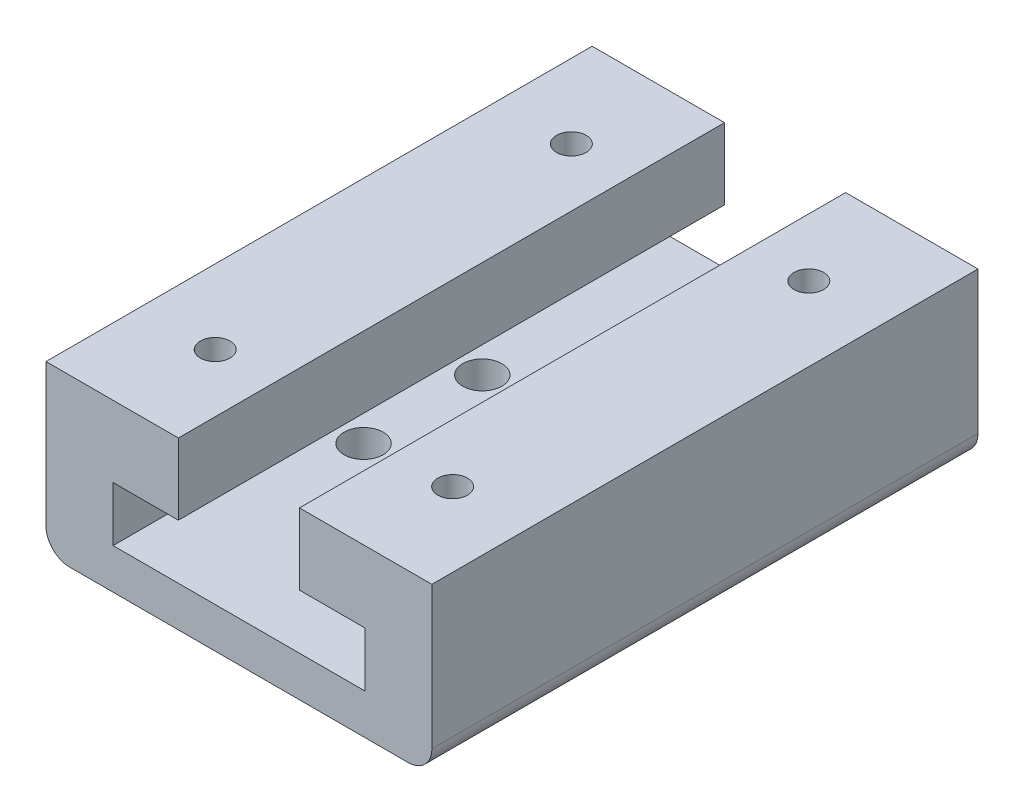
SolidWorks part; units mm, degrees
ref_plane "前视基准面" through (0, 0, 0) normal (0, 0, 1) x (1, 0, 0)
ref_plane "上视基准面" through (0, 0, 0) normal (0, 1, 0) x (1, 0, 0)
ref_plane "右视基准面" through (0, 0, 0) normal (1, 0, 0) x (0, 0, -1)
sketch "草图1" plane through (0, 0, 0) normal (0, 1, 0) x (1, 0, 0)
  line L1 (16.25, -23) -> (-16.25, -23)
  line L2 (16.25, -23) -> (16.25, 23)
  line L3 (16.25, 23) -> (-16.25, 23)
  line L4 (-16.25, -23) -> (-16.25, 23)
  line L5 (16.25, -23) -> (-16.25, 23) construction
  line L6 (16.25, 23) -> (-16.25, -23) construction
  point P0 (0, 0)
  dimension "D1" = 32.5
  dimension "D2" = 46
extrude "凸台-拉伸1" add sketch "草图1" along normal blind 14
sketch "草图2" plane through (0, 0, -23) normal (0, 0, -1) x (-1, 0, 0)
  line L0 (-16.25, 14) -> (16.25, 14) construction
  line L1 (-5.1, 8) -> (5.1, 8)
  line L2 (-5.1, 8) -> (-5.1, 14)
  line L3 (-5.1, 14) -> (5.1, 14)
  line L4 (5.1, 8) -> (5.1, 14)
  line L5 (-5.1, 8) -> (5.1, 14) construction
  line L6 (-5.1, 14) -> (5.1, 8) construction
  line L8 (-10.6, 3.4) -> (10.6, 3.4)
  line L9 (-10.6, 3.4) -> (-10.6, 8)
  line L10 (-10.6, 8) -> (10.6, 8)
  line L11 (10.6, 3.4) -> (10.6, 8)
  line L12 (-10.6, 3.4) -> (10.6, 8) construction
  line L13 (-10.6, 8) -> (10.6, 3.4) construction
  point P0 (0, 11)
  point P9 (0, 5.7)
  line M7 (16.25, 14) -> (-16.25, 14)
  dimension "D1" = 6
  dimension "D2" = 10.2
  dimension "D3" = 21.2
  dimension "D4" = 10.6
  dimension "D5" = 0
extrude "切除-拉伸2" cut sketch "草图2" against normal through all contours L1 L4 L2 M7 | L8 L11 L10 L1 L9
sketch "草图4" plane through (0, 0, 0) normal (0, -1, 0) x (1, 0, 0)
  line L1 (-7.5, -5) -> (7.5, -5) construction
  line L2 (-7.5, -5) -> (-7.5, 5) construction
  line L3 (-7.5, 5) -> (7.5, 5) construction
  line L4 (7.5, -5) -> (7.5, 5) construction
  line L5 (-7.5, -5) -> (7.5, 5) construction
  line L6 (-7.5, 5) -> (7.5, -5) construction
  circle A0 centre (-7.5, 5) radius 1.65
  circle A1 centre (7.5, 5) radius 1.65
  circle A2 centre (7.5, -5) radius 1.65
  circle A3 centre (-7.5, -5) radius 1.65
  point P0 (0, 0)
  dimension "D3" = 3.3
  dimension "D4" = 3.3
  dimension "D5" = 3.3
  dimension "D6" = 3.3
  dimension "D1" = 15
  dimension "D2" = 10
extrude "切除-拉伸3" cut sketch "草图4" against normal up to next
sketch "草图5" plane through (0, 14, 0) normal (0, 1, 0) x (1, 0, 0)
  line L1 (-10, -15) -> (10, -15) construction
  line L2 (-10, -15) -> (-10, 15) construction
  line L3 (-10, 15) -> (10, 15) construction
  line L4 (10, -15) -> (10, 15) construction
  line L5 (-10, -15) -> (10, 15) construction
  line L6 (-10, 15) -> (10, -15) construction
  circle A0 centre (-10, 15) radius 1.25
  circle A1 centre (10, 15) radius 1.25
  circle A2 centre (10, -15) radius 1.25
  circle A3 centre (-10, -15) radius 1.25
  point P0 (0, 0)
  dimension "D3" = 2.5
  dimension "D4" = 2.5
  dimension "D5" = 2.5
  dimension "D6" = 2.5
  dimension "D1" = 30
  dimension "D2" = 20
extrude "切除-拉伸4" cut sketch "草图5" against normal blind 2
fillet "圆角1" radius 2 2 edges at (16.25, 0, 0) (-16.25, 0, 0)
equation "\"33.5.00mm\"=34"
